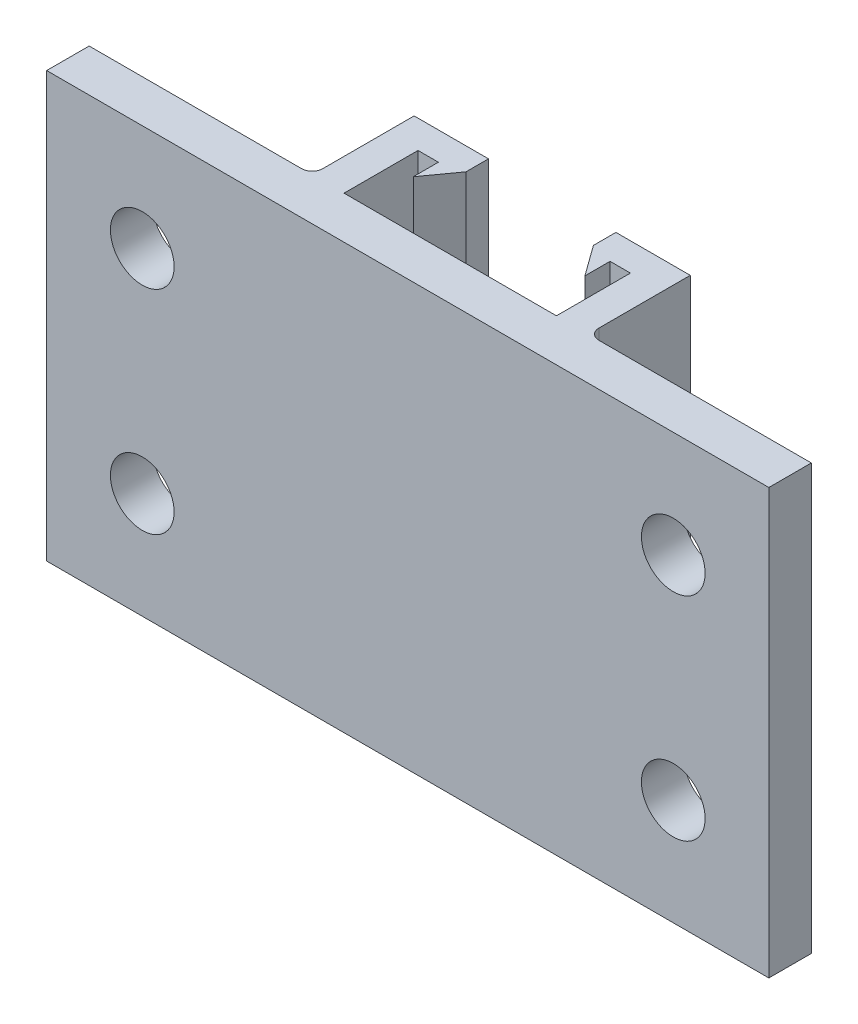
SolidWorks part; units mm, degrees
ref_plane "Alzado" through (0, 0, 0) normal (0, 0, 1) x (1, 0, 0)
ref_plane "Planta" through (0, 0, 0) normal (0, 1, 0) x (1, 0, 0)
ref_plane "Vista lateral" through (0, 0, 0) normal (1, 0, 0) x (0, 0, -1)
sketch "Croquis1" plane through (0, 0, 0) normal (0, 0, 1) x (1, 0, 0)
  line L1 (-17, -10) -> (17, -10)
  line L2 (-17, -10) -> (-17, 10)
  line L3 (-17, 10) -> (17, 10)
  line L4 (17, -10) -> (17, 10)
  line L5 (-17, -10) -> (17, 10) construction
  line L6 (-17, 10) -> (17, -10) construction
  line L7 (-12.5, 5) -> (12.5, 5)
  line L8 (-12.5, 5) -> (-12.5, -5)
  line L9 (-12.5, -5) -> (12.5, -5)
  line L10 (12.5, 5) -> (12.5, -5)
  line L11 (-12.5, 5) -> (12.5, -5) construction
  line L12 (-12.5, -5) -> (12.5, 5) construction
  circle A0 centre (12.5, 5) radius 1.5
  circle A1 centre (-12.5, 5) radius 1.5
  circle A2 centre (-12.5, -5) radius 1.5
  circle A3 centre (12.5, -5) radius 1.5
  point P0 (0, 0)
  point P5 (0, 0)
  dimension "D5" = 3
  dimension "D1" = 20
  dimension "D2" = 34
  dimension "D3" = 25
  dimension "D4" = 10
  dimension "D6" = 2
  dimension "D7" = 2
extrude "Base" add sketch "Croquis1" along normal blind 2 contours L1 L4 L3 L2 A3 L9 A2 L8 A1 L7 A0 L10 | A3 L10 A0 L7 A1 L8 A2 L9
sketch "Croquis2" plane through (0, 10, 0) normal (0, 1, 0) x (1, 0, 0)
  line L0 (-17, 0) -> (17, 0) construction
  line L1 (-5, 0) -> (-6.5, 0)
  line L2 (-5, 0) -> (-5, 3.4827)
  line L4 (-6.5, 0) -> (-6.5, 4.8)
  line L6 (-3, 4.8) -> (-3, 3.7411)
  line L7 (-3, 3.7411) -> (-4.0406, 2.3)
  line L8 (-4.0406, 2.3) -> (-4.0406, 3.4827)
  line L9 (-4.0406, 3.4827) -> (-5, 3.4827)
  line L10 (-3, 4.8) -> (-6.5, 4.8)
  line L11 (0, -1.1) -> (0, 1.1) construction
  line L12 (3, 4.8) -> (6.5, 4.8)
  line L13 (4.0406, 3.4827) -> (5, 3.4827)
  line L14 (4.0406, 2.3) -> (4.0406, 3.4827)
  line L15 (3, 3.7411) -> (4.0406, 2.3)
  line L16 (3, 4.8) -> (3, 3.7411)
  line L17 (6.5, 0) -> (6.5, 4.8)
  line L18 (5, 0) -> (5, 3.4827)
  line L19 (5, 0) -> (6.5, 0)
  dimension "D1" = 5
  dimension "D2" = 4.8
  dimension "D3" = 2.5
  dimension "D4" = 3.5
extrude "Saliente-Extruir2" add sketch "Croquis2" against normal through all
fillet "Redondeo1" radius 0.5 2 edges at (6.5, 0, 0) (-6.5, 0, 0)
